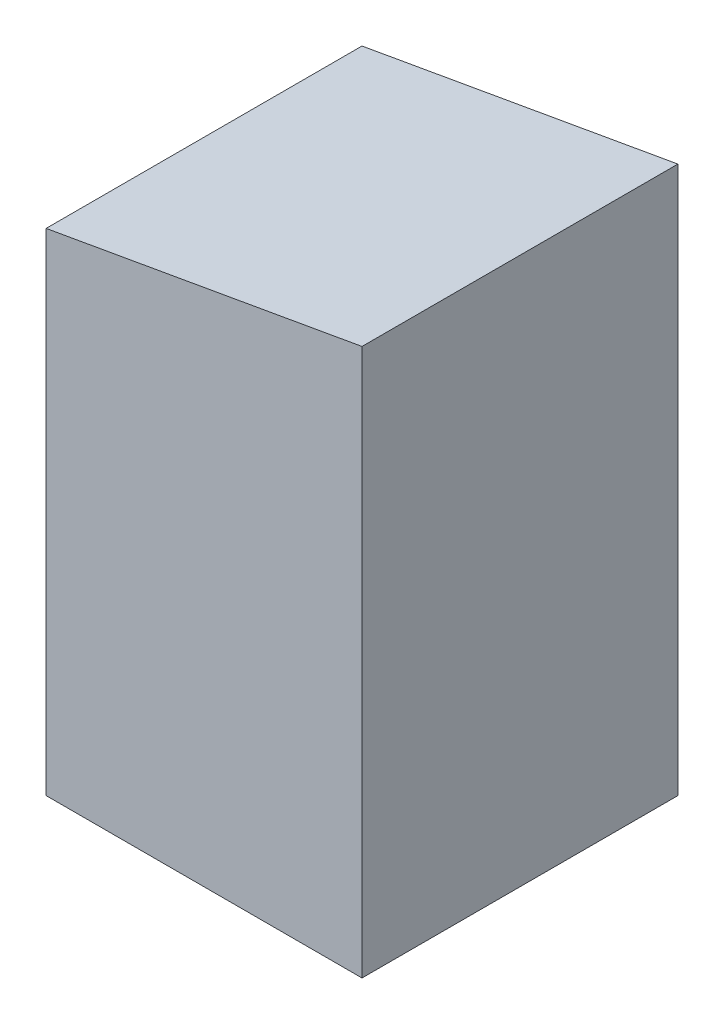
SolidWorks part; units mm, degrees
material "SPF Select 2Btr Grade Lumber"
ref_plane "Front Plane" through (0, 0, 0) normal (0, 0, 1) x (1, 0, 0)
ref_plane "Top Plane" through (0, 0, 0) normal (0, 1, 0) x (1, 0, 0)
ref_plane "Right Plane" through (0, 0, 0) normal (1, 0, 0) x (0, 0, -1)
sketch "Sketch2" plane through (0, 0, 0) normal (0, 0, 1) x (1, 0, 0)
  line L0 (50.8, 87.9574) -> (0, 79)
  line L1 (0, 0) -> (50.8, 0)
  line L2 (0, 0) -> (0, 79)
  line L4 (50.8, 0) -> (50.8, 87.9574)
  dimension "D1" = 50.8
  dimension "D2" = 80
  dimension "D3" = 79
extrude "Boss-Extrude1" add sketch "Sketch2" along normal blind 50.8
